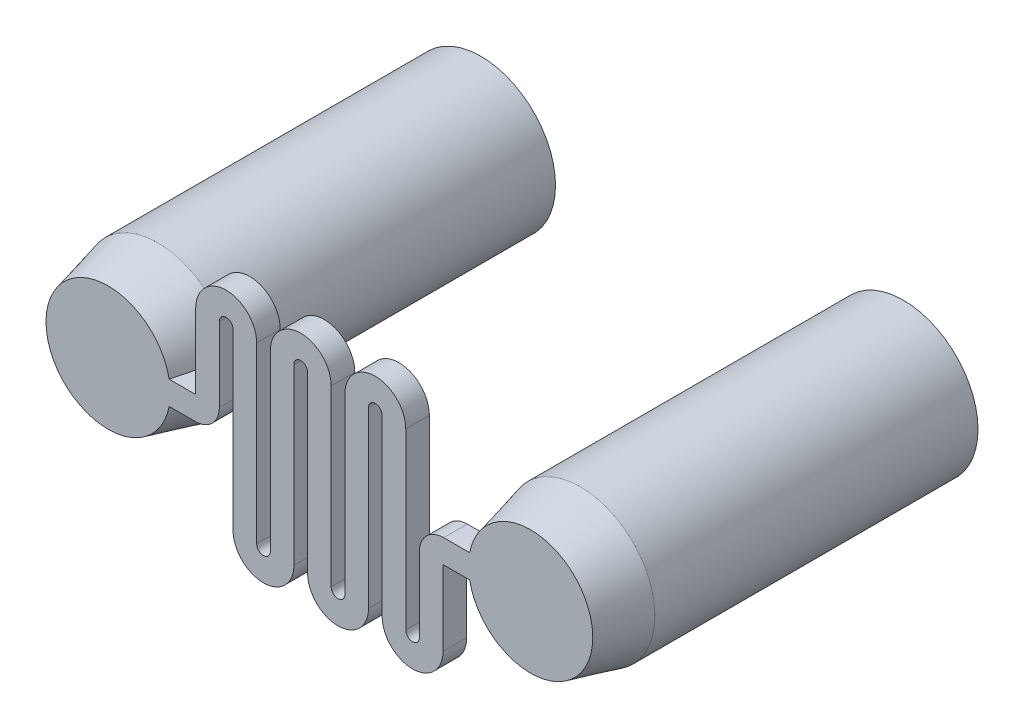
SolidWorks part; units mm, degrees
ref_plane "Front Plane" through (0, 0, 0) normal (0, 0, 1) x (1, 0, 0)
ref_plane "Top Plane" through (0, 0, 0) normal (0, 1, 0) x (1, 0, 0)
ref_plane "Right Plane" through (0, 0, 0) normal (1, 0, 0) x (0, 0, -1)
sketch "Sketch2" plane through (0, 0, 0) normal (0, 0, 1) x (1, 0, 0)
  line L3 (-20.5, -0.95) -> (-13.5, -0.95)
  line L6 (-11.55, 1) -> (-11.55, 7)
  line L9 (-10.45, 7) -> (-10.45, 0)
  line L12 (-10.45, 0) -> (-10.45, -7)
  line L15 (-5.55, -7) -> (-5.55, 0)
  line L18 (-5.55, 0) -> (-5.55, 7)
  line L21 (-4.45, 7) -> (-4.45, 0)
  line L22 (-4.45, 0) -> (-4.45, -7)
  line L23 (0.45, -7) -> (0.45, 0)
  line L24 (0.45, 0) -> (0.45, 7)
  line L25 (1.55, 7) -> (1.55, 0)
  line L26 (1.55, 0) -> (1.55, -7)
  line L27 (6.45, -7) -> (6.45, -1)
  line L28 (6.5, -0.95) -> (13.5, -0.95)
  line L29 (-20.5, 0.95) -> (-13.5, 0.95)
  line L30 (-13.45, 1) -> (-13.45, 7)
  line L31 (-8.55, 7) -> (-8.55, 0)
  line L32 (-8.55, 0) -> (-8.55, -7)
  line L33 (-7.45, -7) -> (-7.45, 0)
  line L34 (-7.45, 0) -> (-7.45, 7)
  line L35 (-2.55, 7) -> (-2.55, 0)
  line L36 (-2.55, 0) -> (-2.55, -7)
  line L37 (-1.45, -7) -> (-1.45, 0)
  line L38 (-1.45, 0) -> (-1.45, 7)
  line L39 (3.45, 7) -> (3.45, 0)
  line L40 (3.45, 0) -> (3.45, -7)
  line L41 (4.55, -7) -> (4.55, -1)
  line L42 (6.5, 0.95) -> (13.5, 0.95)
  arc A0 (13.5, -0.95) -> (13.5, 0.95) centre (13.5, 0) ccw
  arc A8 (-11.55, 1) -> (-13.5, -0.95) centre (-13.5, 1) cw
  arc A9 (-11.55, 7) -> (-10.45, 7) centre (-11, 7) cw
  arc A10 (-10.45, -7) -> (-5.55, -7) centre (-8, -7) ccw
  arc A11 (-5.55, 7) -> (-4.45, 7) centre (-5, 7) cw
  arc A12 (-4.45, -7) -> (0.45, -7) centre (-2, -7) ccw
  arc A13 (0.45, 7) -> (1.55, 7) centre (1, 7) cw
  arc A14 (1.55, -7) -> (6.45, -7) centre (4, -7) ccw
  arc A15 (6.45, -1) -> (6.5, -0.95) centre (6.5, -1) cw
  arc A16 (-13.45, 1) -> (-13.5, 0.95) centre (-13.5, 1) cw
  arc A17 (-13.45, 7) -> (-8.55, 7) centre (-11, 7) cw
  arc A18 (-8.55, -7) -> (-7.45, -7) centre (-8, -7) ccw
  arc A19 (-7.45, 7) -> (-2.55, 7) centre (-5, 7) cw
  arc A20 (-2.55, -7) -> (-1.45, -7) centre (-2, -7) ccw
  arc A21 (-1.45, 7) -> (3.45, 7) centre (1, 7) cw
  arc A22 (3.45, -7) -> (4.55, -7) centre (4, -7) ccw
  arc A23 (4.55, -1) -> (6.5, 0.95) centre (6.5, -1) cw
  arc A24 (-20.5, 0.95) -> (-20.5, -0.95) centre (-20.5, 0) ccw
  point P4 (0, 0)
  point P32 (5.5, 0)
  point P35 (-12.5, 0)
extrude "Boss-Extrude1" add sketch "Sketch2" along normal blind 1.9
ref_plane "Plane1" through (0, 0, 0) normal (0, 1, 0) x (1, 0, 0)
sketch "Sketch3" plane through (0, 0, 0) normal (0, 1, 0) x (1, 0, 0)
  line L0 (-20.5, -1.9) -> (-25.5, -1.9)
  line L2 (-20.5, -1.9) -> (-20.5, 28.1)
  line L3 (-20.5, 28.1) -> (-26.5, 28.1)
  line L4 (-26.5, 28.1) -> (-26.5, 2.1)
  line L5 (-26.5, 2.1) -> (-25.5, -1.9)
  dimension "D1" = 5
  dimension "D3" = 6
  dimension "D4" = 30
revolve "Revolve1" add sketch "Sketch3" angle 360 about L2
ref_plane "Plane2" through (0, 0, 0) normal (0, 1, 0) x (1, 0, 0)
sketch "Sketch4" plane through (0, 0, 0) normal (0, 1, 0) x (1, 0, 0)
  line L0 (13.5, -1.9) -> (18.5, -1.9)
  line L2 (13.5, -1.9) -> (13.5, 28.1)
  line L4 (13.5, 28.1) -> (19.5, 28.1)
  line L5 (19.5, 28.1) -> (19.5, 2.1)
  line L6 (19.5, 2.1) -> (18.5, -1.9)
  dimension "D1" = 6
  dimension "D2" = 5
  dimension "D4" = 30
revolve "Revolve2" add sketch "Sketch4" angle 360 about L2
sketch "Sketch5" plane through (0, 0, -28.1) normal (0, 0, -1) x (-1, 0, 0)
  circle A0 centre (-13.5, 0) radius 5
  circle A1 centre (20.5, 0) radius 5
  dimension "D1" = 10
  dimension "D2" = 10
extrude "Cut-Extrude1" cut sketch "Sketch5" against normal blind 28
